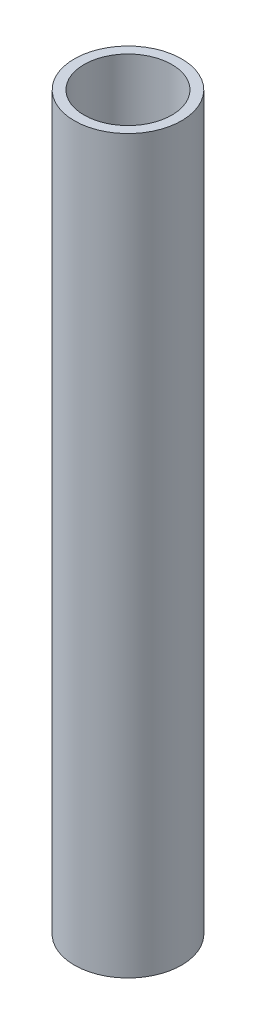
SolidWorks part; units mm, degrees
ref_plane "Front Plane" through (0, 0, 0) normal (0, 0, 1) x (1, 0, 0)
ref_plane "Top Plane" through (0, 0, 0) normal (0, 1, 0) x (1, 0, 0)
ref_plane "Right Plane" through (0, 0, 0) normal (1, 0, 0) x (0, 0, -1)
sketch "Sketch1" plane through (0, 0, 0) normal (0, 1, 0) x (1, 0, 0)
  circle A0 centre (0, 0) radius 11
  circle A1 centre (0, 0) radius 9
  dimension "D1" = 22
  dimension "D2" = 2
extrude "Boss-Extrude1" add sketch "Sketch1" along normal blind 150
